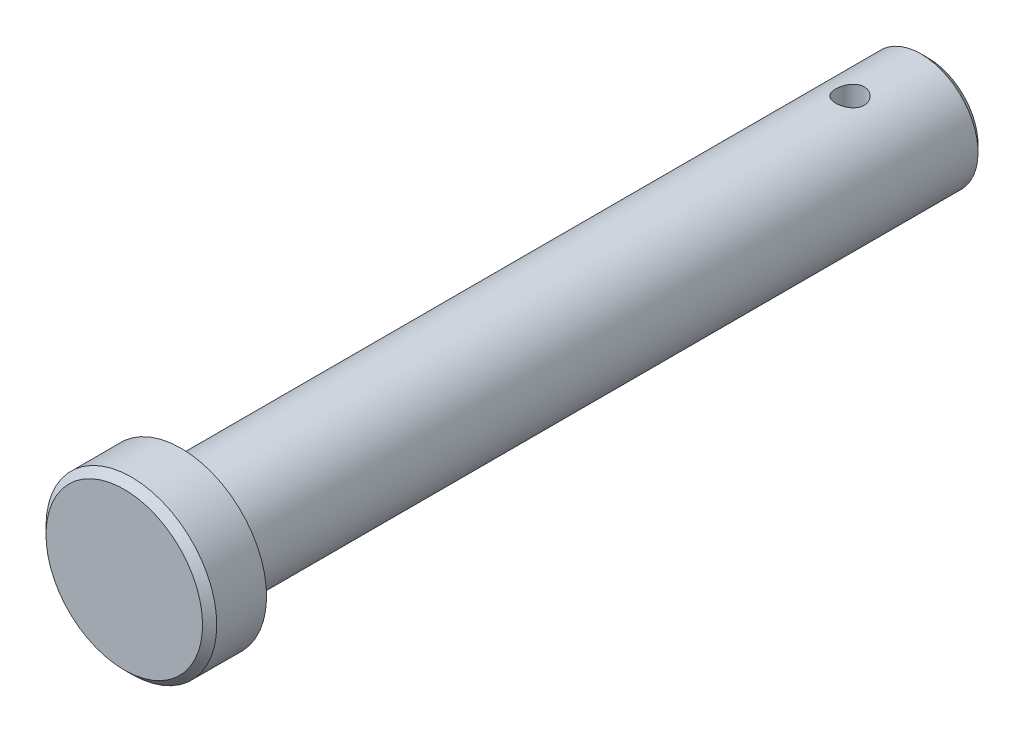
SolidWorks part; units mm, degrees
ref_plane "Front Plane" through (0, 0, 0) normal (0, 0, 1) x (1, 0, 0)
ref_plane "Top Plane" through (0, 0, 0) normal (0, 1, 0) x (1, 0, 0)
ref_plane "Right Plane" through (0, 0, 0) normal (1, 0, 0) x (0, 0, -1)
sketch "Sketch1" plane through (0, 0, 0) normal (1, 0, 0) x (0, 0, -1)
  line L0 (0, 0) -> (0, 12)
  line L1 (0, 12) -> (8, 12)
  line L2 (8, 12) -> (8, 8)
  line L3 (8, 8) -> (113, 8)
  line L4 (113, 8) -> (113, 0)
  line L5 (113, 0) -> (0, 0)
  dimension "D1" = 8
  dimension "D2" = 105
  dimension "D3" = 8
  dimension "D4" = 12
revolve "Revolve1" add sketch "Sketch1" angle 360 about L5
sketch "Sketch2" plane through (0, 0, 0) normal (0, 1, 0) x (1, 0, 0)
  line L0 (12, 8) -> (-12, 8) construction
  circle A0 centre (0, 102) radius 2
  dimension "D1" = 4
  dimension "D2" = 94
extrude "Cut-Extrude1" cut sketch "Sketch2" against normal through all both and the other way through all
chamfer "Chamfer1" distance 1 angle 45 2 edges at (0, 8, -113) (0, 12, 0)
